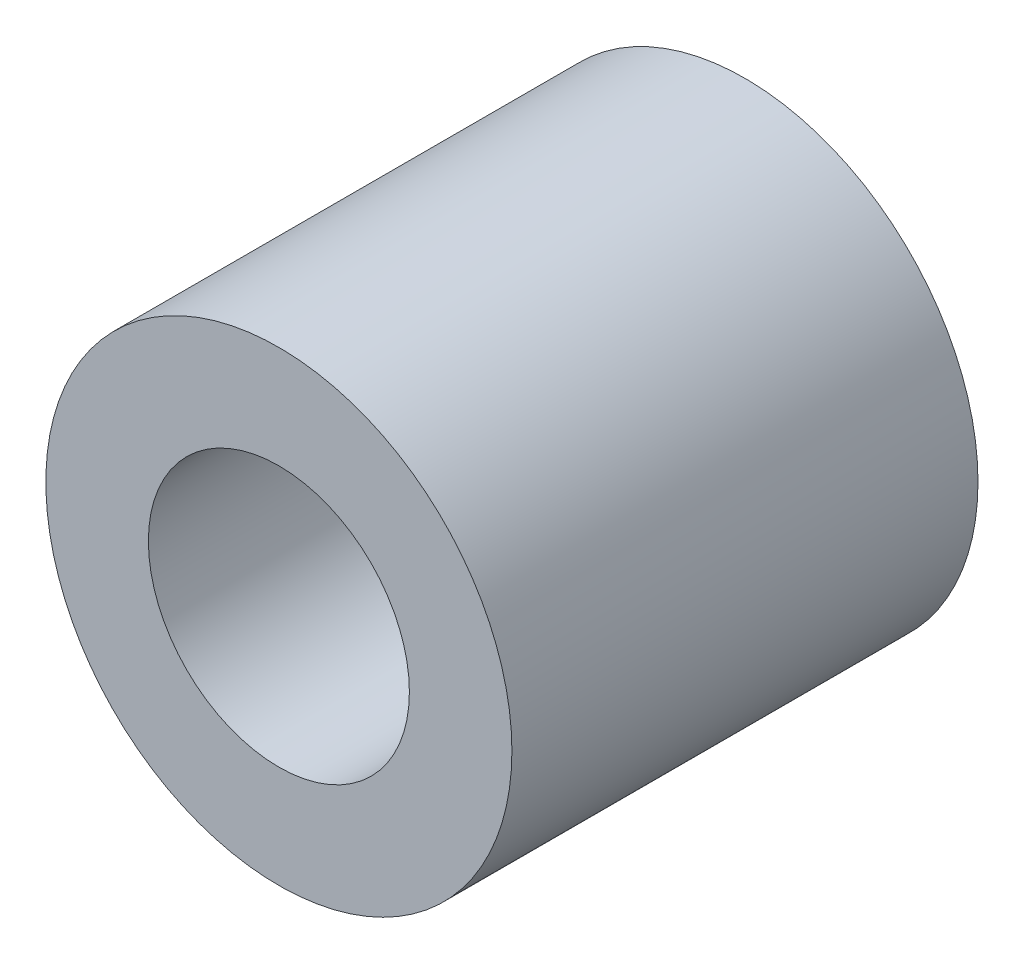
SolidWorks part; units mm, degrees
ref_plane "Front Plane" through (0, 0, 0) normal (0, 0, 1) x (1, 0, 0)
ref_plane "Top Plane" through (0, 0, 0) normal (0, 1, 0) x (1, 0, 0)
ref_plane "Right Plane" through (0, 0, 0) normal (1, 0, 0) x (0, 0, -1)
sketch "Sketch1" plane through (0, 0, 0) normal (0, 0, 1) x (1, 0, 0)
  circle A0 centre (0, 0) radius 3.175
  circle A1 centre (0, 0) radius 1.778
  dimension "OD" = 6.35
  dimension "ID" = 3.556
extrude "Extrude1" add sketch "Sketch1" along normal mid plane 6.35
sketch "Sketch2" plane through (0, 0, 0) normal (1, 0, 0) x (0, 0, -1)
  line L0 (-3.175, -1.778) -> (3.175, -1.778) construction
  line L3 (3.175, 1.778) -> (-3.175, 1.778) construction
  line L5 (-3.175, -1.778) -> (3.175, -1.778)
  line L6 (3.175, 1.778) -> (-3.175, 1.778)
sketch "Sketch4" plane through (0, 0, 3.175) normal (0, 0, 1) x (1, 0, 0)
  line L0 (0, 0) -> (-1.2572, 1.2572)
  line L1 (0, -2.6194) -> (0, 2.6194) construction
  circle A0 centre (0, 0) radius 1.778 construction
  dimension "D1" = 45
